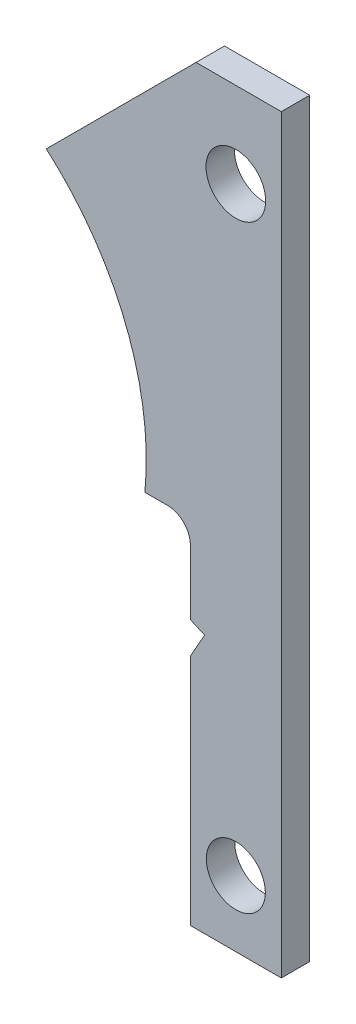
SolidWorks part; units mm, degrees
ref_plane "Front Plane" through (0, 0, 0) normal (0, 0, 1) x (1, 0, 0)
ref_plane "Top Plane" through (0, 0, 0) normal (0, 1, 0) x (1, 0, 0)
ref_plane "Right Plane" through (0, 0, 0) normal (1, 0, 0) x (0, 0, -1)
sketch "Model" plane through (0, 0, 0) normal (0, 0, 1) x (1, 0, 0)
  line L0 (869.6, 129.8) -> (854.6, 129.8)
  line L1 (854.6, 129.8) -> (854.6, 124.8)
  line L2 (820.0281, 59.8) -> (849.6, 59.8)
  line L3 (853.6, 55.8) -> (853.6, 44.4002)
  line L4 (853.6, 44.4002) -> (856.1, 43.3)
  line L5 (856.1, 43.3) -> (853.6, 38.8294)
  line L6 (853.6, 38.8294) -> (853.6, -2.2)
  line L7 (853.6, -2.2) -> (869.6, -2.2)
  line L8 (869.6, -2.2) -> (869.6, 129.8)
  arc A0 (815.1233, 79.1972) -> (854.6, 124.8) centre (806.7231, 126.3571) ccw
  arc A1 (820.0281, 59.8) -> (815.1233, 79.1972) centre (795.0764, 63.8094) ccw
  arc A2 (853.6, 55.8) -> (849.6, 59.8) centre (849.6, 55.8) ccw
  circle A3 centre (861.6, 9.3915) radius 5.1919
  circle A4 centre (861.6, 114.8) radius 5.25
extrude "Boss-Extrude1" add sketch "Model" along normal blind 5
sketch "Sketch4" plane through (0, 0, 0) normal (0, 0, 1) x (1, 0, 0)
  line L0 (854.6, 129.8) -> (799.7005, 74.9005)
  line L1 (799.7005, 74.9005) -> (857.0819, 78.4517)
  line L2 (857.0819, 78.4517) -> (855.6766, 119.4362)
  line L3 (855.6766, 119.4362) -> (858.6479, 128.485)
  line L4 (858.6479, 128.485) -> (854.6, 129.8)
extrude "Boss-Extrude2" add sketch "Sketch4" along normal blind 5
sketch "Sketch3" plane through (0, 0, 0) normal (0, 0, -1) x (-1, 0, 0)
  circle A1 centre (-861.6, 114.8) radius 5.25 construction
  circle A2 centre (-794.6, 64.8) radius 51.25
  dimension "D1" = 67
  dimension "D2" = 50
extrude "Cut-Extrude1" cut sketch "Sketch3" against normal blind 6
